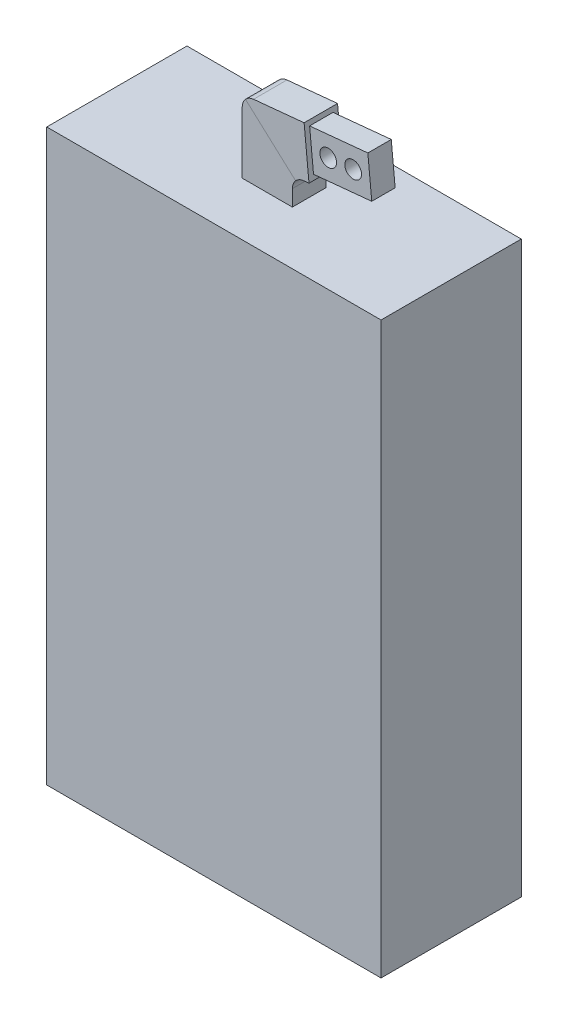
SolidWorks part; units mm, degrees
ref_plane "Front Plane" through (0, 0, 0) normal (0, 0, 1) x (1, 0, 0)
ref_plane "Top Plane" through (0, 0, 0) normal (0, 1, 0) x (1, 0, 0)
ref_plane "Right Plane" through (0, 0, 0) normal (1, 0, 0) x (0, 0, -1)
sketch "Sketch1" plane through (0, 0, 0) normal (0, 1, 0) x (1, 0, 0)
  line L1 (100, -41.945) -> (-100, -41.945)
  line L2 (100, -41.945) -> (100, 41.945)
  line L3 (100, 41.945) -> (-100, 41.945)
  line L4 (-100, -41.945) -> (-100, 41.945)
  line L5 (100, -41.945) -> (-100, 41.945) construction
  line L6 (100, 41.945) -> (-100, -41.945) construction
  point P0 (0, 0)
  dimension "D1" = 200
  dimension "D2" = 83.89
extrude "Wheel & Steering Dummy" add sketch "Sketch1" against normal blind 340.92
sketch "Sketch3" plane through (0, 0, 0) normal (0, 0, 1) x (1, 0, 0)
  line L0 (0, 0) -> (0, 30)
  line L1 (0, 30) -> (58.3282, 35.6987)
  line L2 (0, 30) -> (50, 30) construction
  dimension "D1" = 50
  dimension "D2" = 30
  dimension "D3" = 58.6059
  dimension "D4" = 5.58
sketch "Sketch4" plane through (0, 0, 0) normal (0, 1, 0) x (1, 0, 0)
  line L1 (15, -10) -> (-15, -10)
  line L2 (15, -10) -> (15, 10)
  line L3 (15, 10) -> (-15, 10)
  line L4 (-15, -10) -> (-15, 10)
  line L5 (15, -10) -> (-15, 10) construction
  line L6 (15, 10) -> (-15, -10) construction
  point P0 (0, 0)
  dimension "D1" = 30
  dimension "D2" = 20
sweep "Mount Body" add profiles "Sketch4" path "Sketch3"
sketch "Sketch5" plane through (61.2315, 5.9823, 0) normal (0.9953, 0.0972, 0) x (0, 0, -1)
  line L1 (-10, 44.8578) -> (10, 44.8578)
  line L2 (-10, 44.8578) -> (-10, 14.8578)
  line L3 (-10, 14.8578) -> (10, 14.8578)
  line L4 (10, 44.8578) -> (10, 14.8578)
  line L5 (7, 17.8578) -> (-7, 17.8578)
  line L6 (7, 17.8578) -> (7, 41.8578)
  line L7 (7, 41.8578) -> (-7, 41.8578)
  line L8 (-7, 17.8578) -> (-7, 41.8578)
  line L9 (7, 17.8578) -> (-7, 41.8578) construction
  line L10 (7, 41.8578) -> (-7, 17.8578) construction
  point P6 (0, 29.8578)
  dimension "D1" = 3
  dimension "D2" = 3
  dimension "D3" = 3
  dimension "D4" = 3
extrude "Mount Tongue" cut sketch "Sketch5" against normal blind 35
sketch "Sketch6" plane through (0, 0, 7) normal (0, 0, 1) x (1, 0, 0)
  line L0 (23.4941, 32.2954) -> (58.3282, 35.6987) construction
  line L1 (22.0355, 47.2243) -> (24.9526, 17.3665) construction
  line L2 (57.1614, 47.6418) -> (59.495, 23.7555) construction
  circle A0 centre (33.4467, 33.2677) radius 5
  circle A1 centre (48.3756, 34.7263) radius 5
  dimension "D1" = 10
  dimension "D2" = 10
  dimension "D3" = 10
  dimension "D4" = 10
extrude "Mount Holes" cut sketch "Sketch6" against normal through all
fillet "Fillet1" radius 7.5 2 edges at (15, 16.3941, 0) (-15, 43.6059, 0)
equation "\"neck_height\"= 30.0mm"
equation "\"arm_length\"= 58.60591964945572mm"
equation "\"angle\"= 5.580088106667777"
equation "\"width\"= 30.0mm"
equation "\"mount_thickness\"= 20.0mm"
equation "\"fillet_radius\"= 7.5mm"
equation "\"linkage_mount_tongue_length\"= 35.0mm"
equation "\"linkage_mount_shoulder_depth\"= 3.0mm"
equation "\"linkage_mount_bolt_diameter\"= 10.0mm"
equation "\"linkage_mount_bolt_spacing\"= 5.0mm"
equation "\"D2@Sketch3\"=\"neck_height\""
equation "\"D3@Sketch3\"=\"arm_length\""
equation "\"D4@Sketch3\"=\"angle\""
equation "\"D1@Sketch4\"=\"width\""
equation "\"D2@Sketch4\"=\"mount_thickness\""
equation "\"D1@Sketch5\"=\"linkage_mount_shoulder_depth\""
equation "\"D2@Sketch5\"=\"linkage_mount_shoulder_depth\""
equation "\"D3@Sketch5\"=\"linkage_mount_shoulder_depth\""
equation "\"D4@Sketch5\"=\"linkage_mount_shoulder_depth\""
equation "\"D1@Mount Tongue\"=\"linkage_mount_tongue_length\""
equation "\"D1@Sketch6\"=\"linkage_mount_bolt_diameter\""
equation "\"D2@Sketch6\"=\"linkage_mount_bolt_diameter\""
equation "\"D3@Sketch6\"=\"linkage_mount_bolt_spacing\"+\"linkage_mount_bolt_diameter\"/2"
equation "\"D4@Sketch6\"=\"linkage_mount_bolt_spacing\"+\"linkage_mount_bolt_diameter\"/2"
equation "\"D1@Fillet1\"=\"fillet_radius\""
